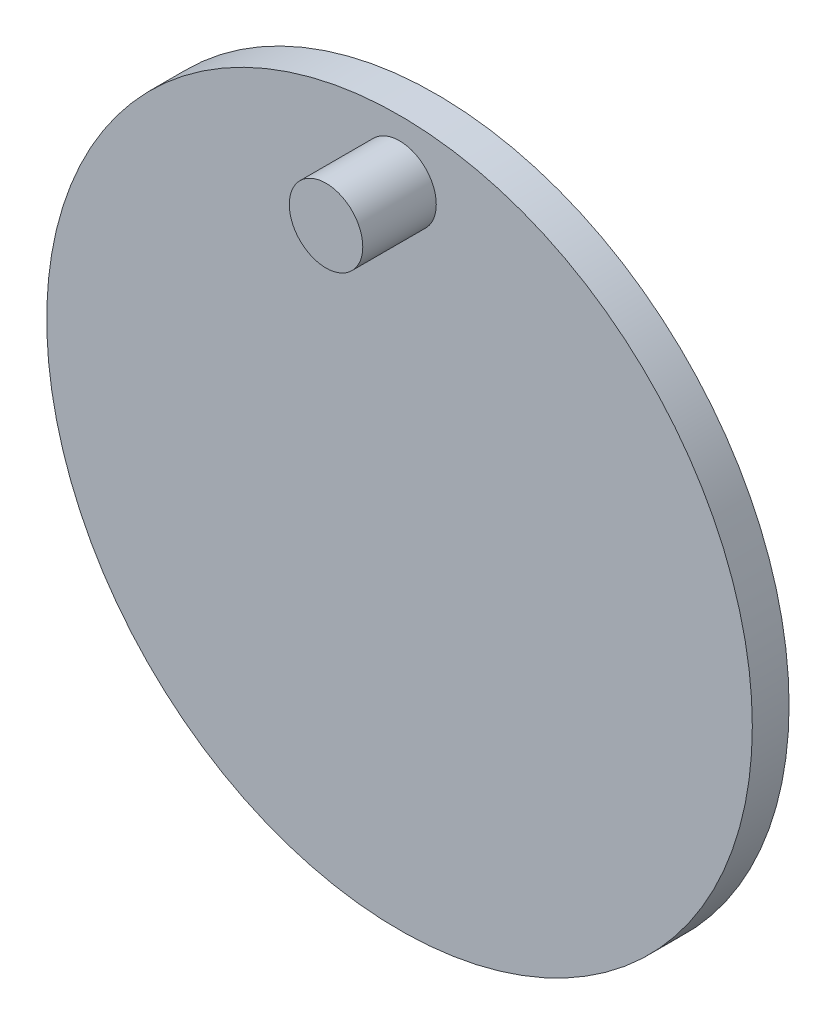
SolidWorks part; units mm, degrees
ref_plane "Plano frontal" through (0, 0, 0) normal (0, 0, 1) x (1, 0, 0)
ref_plane "Plano superior" through (0, 0, 0) normal (0, 1, 0) x (1, 0, 0)
ref_plane "Plano direito" through (0, 0, 0) normal (1, 0, 0) x (0, 0, -1)
sketch "Esboço1" plane through (0, 0, 0) normal (0, 0, 1) x (1, 0, 0)
  line L0 (-48, 0) -> (48, 0) construction
  line L1 (0, 48) -> (0, -48) construction
  circle A0 centre (0, 0) radius 48
  dimension "D1" = 96
extrude "Ressalto-extrusão1" add sketch "Esboço1" along normal blind 5
sketch "Esboço2" plane through (0, 0, 0) normal (0, 0, 1) x (1, 0, 0)
  line L0 (-52.6575, 0) -> (53.5615, 0) construction
  line L1 (0, 53.5615) -> (0, -52.6575) construction
  line L2 (0.452, 0) -> (0, 40)
  circle A0 centre (0, 40) radius 5
  point P8 (0, 0)
  dimension "D2" = 10
  dimension "D1" = 40
extrude "Ressalto-extrusão2" add sketch "Esboço2" along normal blind 15
sketch "Esboço3" plane through (0, 0, 0) normal (0, 0, -1) x (-1, 0, 0)
  circle A0 centre (0, 0) radius 10
  dimension "D1" = 20
extrude "Ressalto-extrusão4" add sketch "Esboço3" along normal blind 10
